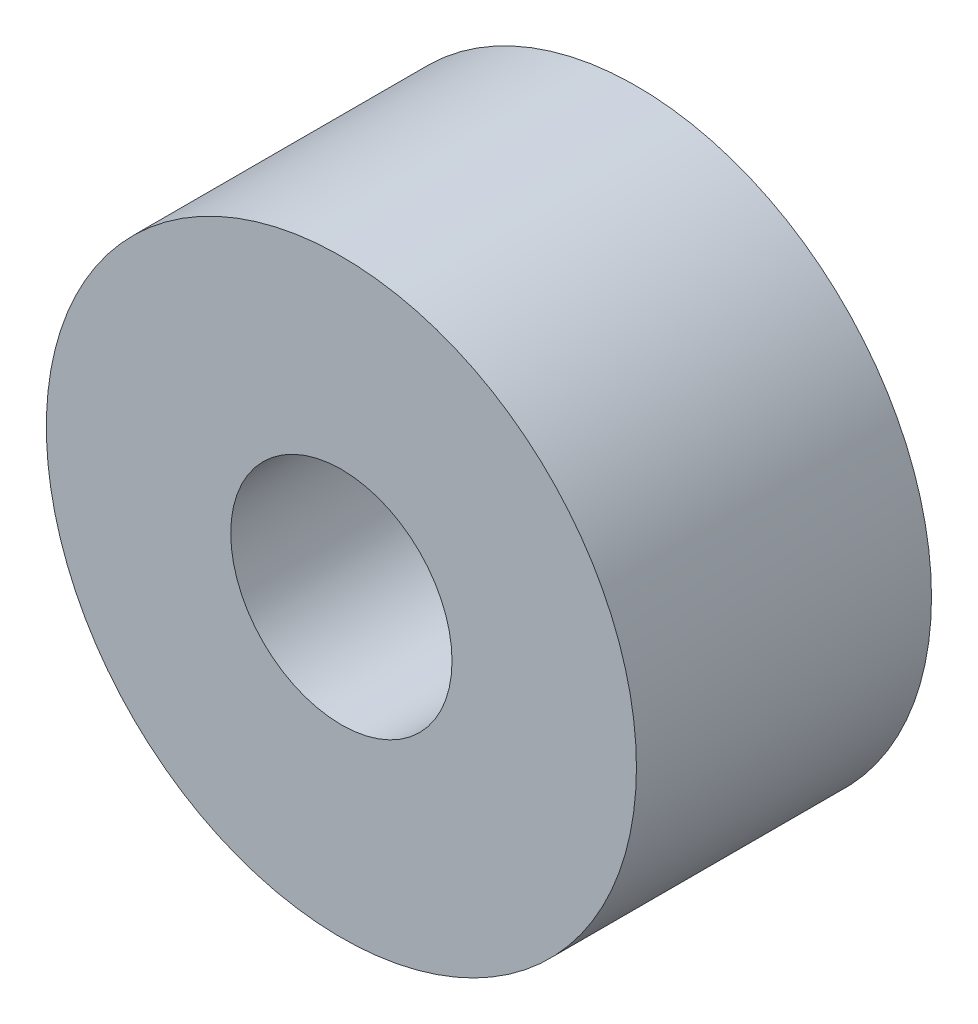
SolidWorks part; units mm, degrees
material "6061 Alloy"
ref_plane "Front Plane" through (0, 0, 0) normal (0, 0, 1) x (1, 0, 0)
ref_plane "Top Plane" through (0, 0, 0) normal (0, 1, 0) x (1, 0, 0)
ref_plane "Right Plane" through (0, 0, 0) normal (1, 0, 0) x (0, 0, -1)
sketch "Sketch1" plane through (0, 0, 0) normal (0, 0, 1) x (1, 0, 0)
  circle A0 centre (0, 0) radius 2.3813
  circle A1 centre (0, 0) radius 6.35
  point P0 (0, 0)
  dimension "D2" = 4.7625
  dimension "D1" = 12.7
extrude "Boss-Extrude1" add sketch "Sketch1" along normal blind 6.35
